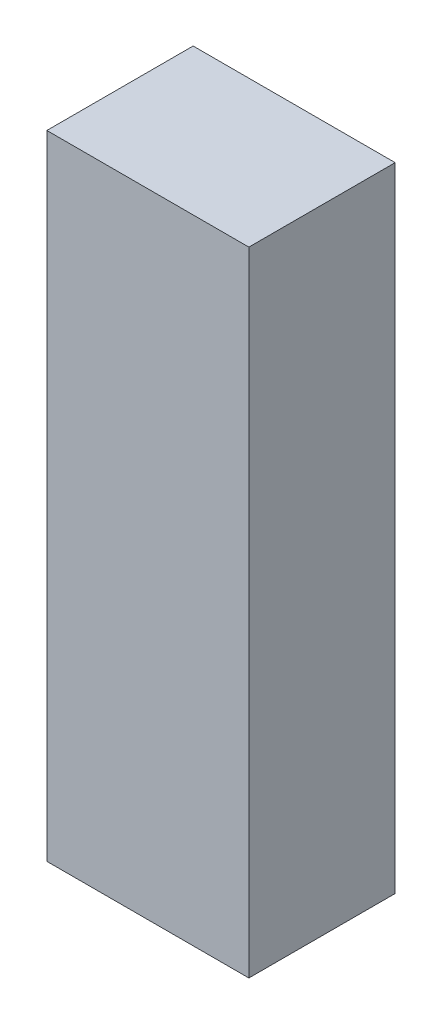
SolidWorks part; units mm, degrees
ref_plane "Front Plane" through (0, 0, 0) normal (0, 0, 1) x (1, 0, 0)
ref_plane "Top Plane" through (0, 0, 0) normal (0, 1, 0) x (1, 0, 0)
ref_plane "Right Plane" through (0, 0, 0) normal (1, 0, 0) x (0, 0, -1)
sketch "Sketch1" plane through (0, 0, 0) normal (0, 1, 0) x (1, 0, 0)
  line L1 (-17.5387, -12.7) -> (17.5387, -12.7)
  line L2 (-17.5387, -12.7) -> (-17.5387, 12.7)
  line L3 (-17.5387, 12.7) -> (17.5387, 12.7)
  line L4 (17.5387, -12.7) -> (17.5387, 12.7)
  line L5 (-17.5387, -12.7) -> (17.5387, 12.7) construction
  line L6 (-17.5387, 12.7) -> (17.5387, -12.7) construction
  point P0 (0, 0)
  dimension "D1" = 25.4
  dimension "D2" = 35.0774
extrude "Boss-Extrude1" add sketch "Sketch1" along normal blind 109.9058
